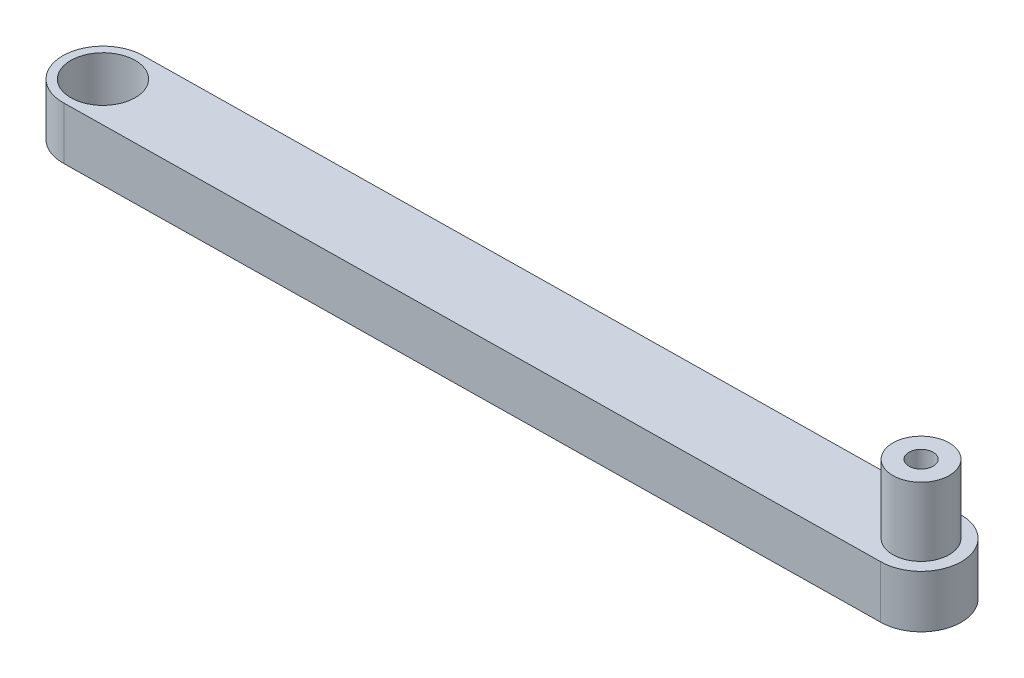
SolidWorks part; units mm, degrees
ref_plane "前视基准面" through (0, 0, 0) normal (0, 0, 1) x (1, 0, 0)
ref_plane "上视基准面" through (0, 0, 0) normal (0, 1, 0) x (1, 0, 0)
ref_plane "右视基准面" through (0, 0, 0) normal (1, 0, 0) x (0, 0, -1)
other "Configuration Table"
sketch "草图1" plane through (0, 0, 0) normal (0, 1, 0) x (1, 0, 0)
  line L0 (0, 0) -> (99.9903, 1.3894)
  line L1 (0, 5) -> (99.9903, 6.3894)
  line L2 (0, -5) -> (99.9903, -3.6106)
  circle A0 centre (0, 0) radius 4
  circle A1 centre (0, 0) radius 5
  circle A2 centre (99.9903, 1.3894) radius 5
  dimension "D1" = 8
  dimension "D2" = 10
  dimension "D4" = 10
  dimension "D3" = 100
extrude "凸台-拉伸1" add sketch "草图1" along normal blind 6.5
sketch "草图2" plane through (0, 6.5, 0) normal (0, 1, 0) x (1, 0, 0)
  circle A0 centre (99.9903, 1.3894) radius 3.5
  dimension "D1" = 7
extrude "凸台-拉伸2" add sketch "草图2" along normal blind 8.5
sketch "草图3" plane through (0, 15, 0) normal (0, 1, 0) x (1, 0, 0)
  circle A0 centre (99.9903, 1.3894) radius 1.5
  dimension "D1" = 3
extrude "切除-拉伸1" cut sketch "草图3" against normal through all
